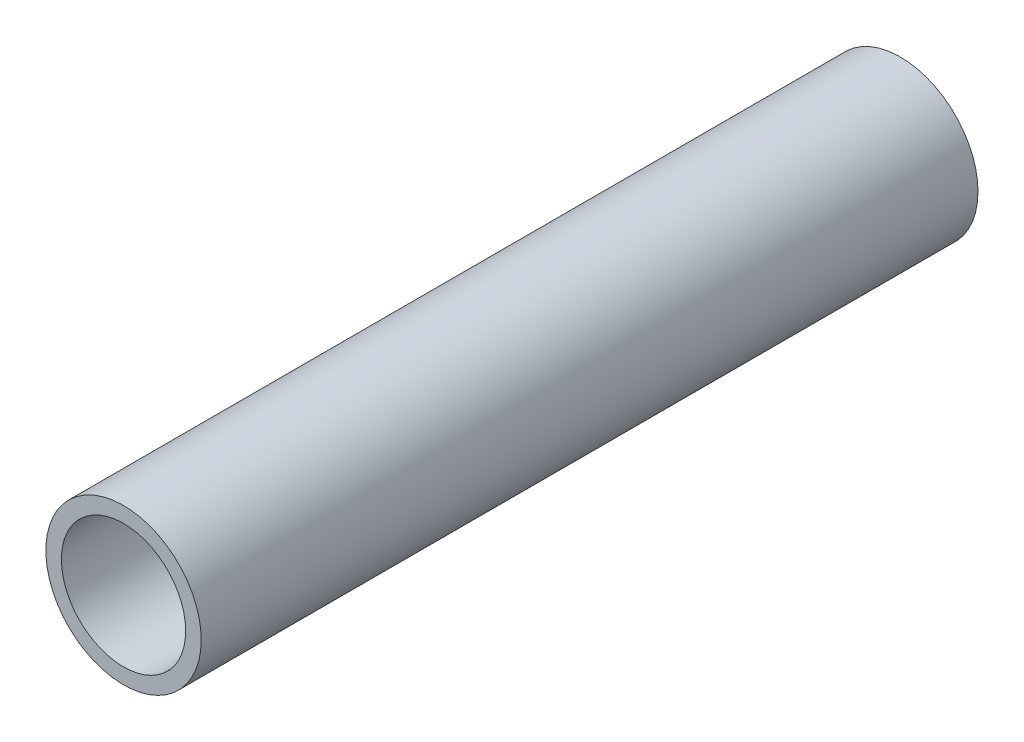
SolidWorks part; units mm, degrees
material "Thornel Mat VMA"
ref_plane "Płaszczyzna przednia" through (0, 0, 0) normal (0, 0, 1) x (1, 0, 0)
ref_plane "Płaszczyzna górna" through (0, 0, 0) normal (0, 1, 0) x (1, 0, 0)
ref_plane "Płaszczyzna prawa" through (0, 0, 0) normal (1, 0, 0) x (0, 0, -1)
sketch "Szkic1" plane through (0, 0, 0) normal (0, 0, 1) x (1, 0, 0)
  circle A0 centre (0, 0) radius 12
  circle A1 centre (0, 0) radius 15
  dimension "D1" = 3
  dimension "D2" = 30
extrude "Dodanie-wyciągnięcie1" add sketch "Szkic1" along normal blind 150
